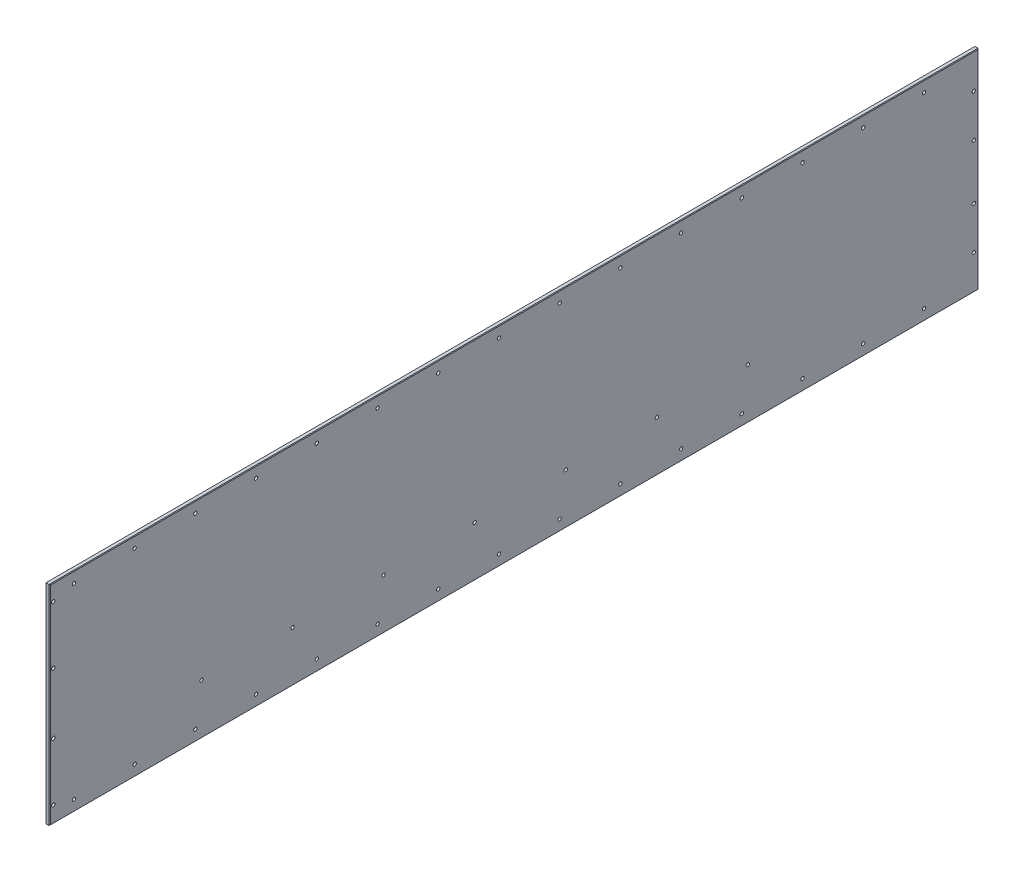
SolidWorks part; units mm, degrees
material "1060 Legierung"
ref_plane "Front Plane" through (0, 0, 0) normal (0, 0, 1) x (1, 0, 0)
ref_plane "Top Plane" through (0, 0, 0) normal (0, 1, 0) x (1, 0, 0)
ref_plane "Right Plane" through (0, 0, 0) normal (1, 0, 0) x (0, 0, -1)
sketch "Sketch1" plane through (0, 0, 0) normal (1, 0, 0) x (0, 0, -1)
  line L0 (0, 0) -> (59.3183, 0) construction
  line L1 (0, 28.1909) -> (0, -28.8956) construction
  line L2 (-765, 172) -> (765, 172)
  line L3 (765, 172) -> (765, -172)
  line L4 (765, -172) -> (-765, -172)
  line L5 (-765, -172) -> (-765, 172)
  dimension "D1" = 1530
  dimension "D2" = 344
extrude "Boss-Extrude1" add sketch "Sketch1" along normal blind 6
chamfer "Fase1" distance 1 angle 45 4 edges at (6, -172, 0) (6, 172, 0) (6, 0, 765) (6, 0, -765)
hole_wizard "CSK for M5 Countersunk Raised Head Screw1" positions "Skizze2" profile "Skizze1" countersink size "M5" standard "DIN" end condition through all
sketch "Skizze2" plane through (0, 0, 0) normal (-1, 0, 0) x (0, 0, 1)
  line L0 (-785.2095, 0) -> (-327.2707, 0) construction
  line L2 (-765, -172) -> (-765, 172) construction
  line L3 (765, 172) -> (765, -172) construction
  point P0 (-757, 115)
  point P2 (-757, 45)
  point P11 (759, 145)
  point P13 (759, 50)
  dimension "D1" = 45
  dimension "D2" = 115
  dimension "D3" = 8
  dimension "D4" = 8
  dimension "D5" = 6
  dimension "D6" = 6
  dimension "D7" = 50
  dimension "D8" = 145
sketch "Skizze1" plane through (0, 115, -757) normal (0, 1, 0) x (0, 0, 1)
  line L0 (0, 0) -> (0, 6)
  line L1 (0, 6) -> (2.75, 6)
  line L2 (2.75, 6) -> (2.75, 2.45)
  line L3 (2.75, 2.45) -> (5.2, 0)
  line L5 (5.2, 0) -> (0, 0)
  line L6 (-2.75, 2.45) -> (-5.2, 0) construction
  line L11 (0, -6.35) -> (0, 107.95) construction
  dimension "Bohrerdurchmesser" = 5.5
  dimension "Bohrungstiefe" = 6
  dimension "Senkdurchmesser (Oben)" = 10.4
  dimension "Senkwinkel (Oben)" = 90
hole_wizard "CSK for M5 Countersunk Raised Head Screw2" positions "Sketch3" profile "Sketch2" countersink size "M5" standard "DIN" end condition through all
sketch "Sketch3" plane through (0, 0, 0) normal (-1, 0, 0) x (0, 0, 1)
  line L0 (-765, 172) -> (765, 172) construction
  line L1 (765, 172) -> (765, -172) construction
  point P0 (725, 154)
  dimension "D1" = 18
  dimension "D2" = 40
sketch "Sketch2" plane through (0, 154, 725) normal (0, 1, 0) x (0, 0, 1)
  line L0 (0, 0) -> (0, 6)
  line L1 (0, 6) -> (2.75, 6)
  line L2 (2.75, 6) -> (2.75, 2.45)
  line L3 (2.75, 2.45) -> (5.2, 0)
  line L5 (5.2, 0) -> (0, 0)
  line L6 (-2.75, 2.45) -> (-5.2, 0) construction
  line L11 (0, -6.35) -> (0, 107.95) construction
  dimension "Thru Hole Dia." = 5.5
  dimension "Thru Hole Depth" = 6
  dimension "Near C'Sink Dia." = 10.4
  dimension "Near C'Sink Angle" = 90
pattern_linear "LPattern1" count 15 spacing 100 along (0, 0, -1) of "CSK for M5 Countersunk Raised Head Screw2"
mirror "Spiegeln1" about plane through (0, 0, 0) normal (0, 1, 0) of "LPattern1", "CSK for M5 Countersunk Raised Head Screw1", "CSK for M5 Countersunk Raised Head Screw2"
hole_wizard "CSK for M5 Countersunk Raised Head Screw3" positions "Skizze4" profile "Skizze3" countersink size "M5" standard "DIN" end condition through all
sketch "Skizze4" plane through (0, 0, 0) normal (-1, 0, 0) x (0, 0, 1)
  line L0 (765, -172) -> (-765, -172) construction
  line L1 (765, 172) -> (765, -172) construction
  point P0 (515, -89)
  dimension "D1" = 83
  dimension "D2" = 250
sketch "Skizze3" plane through (0, -89, 515) normal (0, 1, 0) x (0, 0, 1)
  line L0 (0, 0) -> (0, 6)
  line L1 (0, 6) -> (2.75, 6)
  line L2 (2.75, 6) -> (2.75, 2.45)
  line L3 (2.75, 2.45) -> (5.2, 0)
  line L5 (5.2, 0) -> (0, 0)
  line L6 (-2.75, 2.45) -> (-5.2, 0) construction
  line L11 (0, -6.35) -> (0, 107.95) construction
  dimension "Bohrerdurchmesser" = 5.5
  dimension "Bohrungstiefe" = 6
  dimension "Senkdurchmesser (Oben)" = 10.4
  dimension "Senkwinkel (Oben)" = 90
pattern_linear "Lineares Muster1" count 7 spacing 150 along (0, 0, -1) of "CSK for M5 Countersunk Raised Head Screw3"
